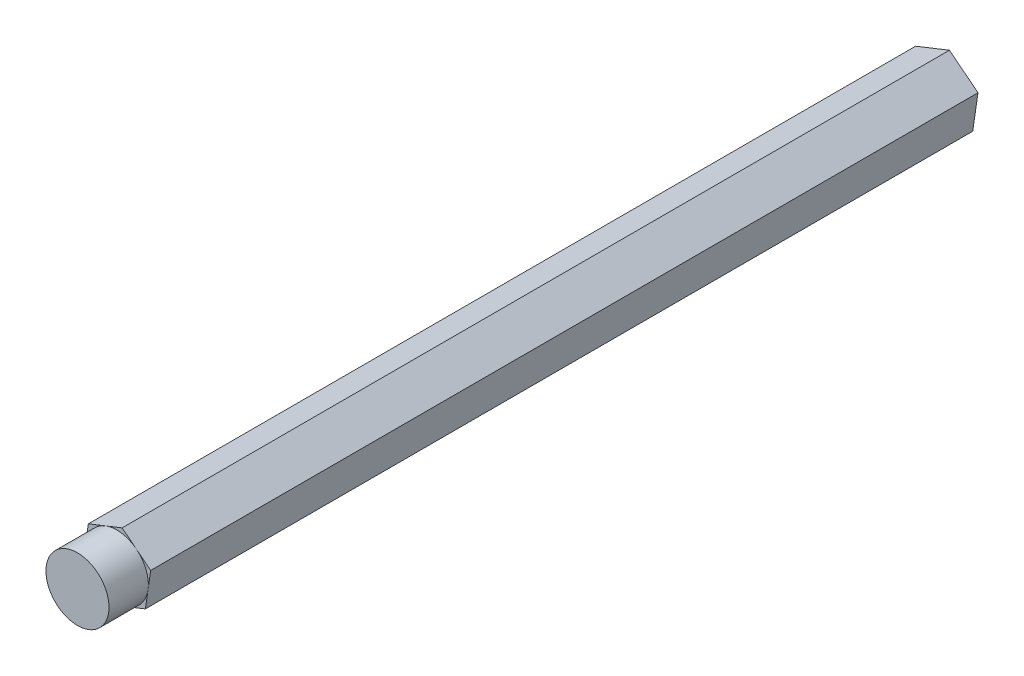
SolidWorks part; units mm, degrees
ref_plane "Front Plane" through (0, 0, 0) normal (0, 0, 1) x (1, 0, 0)
ref_plane "Top Plane" through (0, 0, 0) normal (0, 1, 0) x (1, 0, 0)
ref_plane "Right Plane" through (0, 0, 0) normal (1, 0, 0) x (0, 0, -1)
sketch "Sketch1" plane through (0, 0, 0) normal (0, 0, 1) x (1, 0, 0)
  line L1 (1.0649, 7.2546) -> (-5.7502, 4.5495)
  line L2 (-5.7502, 4.5495) -> (-6.8151, -2.7051)
  line L3 (-6.8151, -2.7051) -> (-1.0649, -7.2546)
  line L4 (-1.0649, -7.2546) -> (5.7502, -4.5495)
  line L5 (5.7502, -4.5495) -> (6.8151, 2.7051)
  line L6 (6.8151, 2.7051) -> (1.0649, 7.2546)
  circle A0 centre (0, 0) radius 6.35 construction
  dimension "D1" = 12.7
extrude "Boss-Extrude1" add sketch "Sketch1" along normal blind 174.6377
sketch "Sketch2" plane through (0, 0, 174.6377) normal (0, 0, 1) x (1, 0, 0)
  circle A0 centre (0, 0) radius 6.35
  circle A1 centre (0, 0) radius 7.3323
extrude "Cut-Extrude1" cut sketch "Sketch2" against normal blind 7.9375
